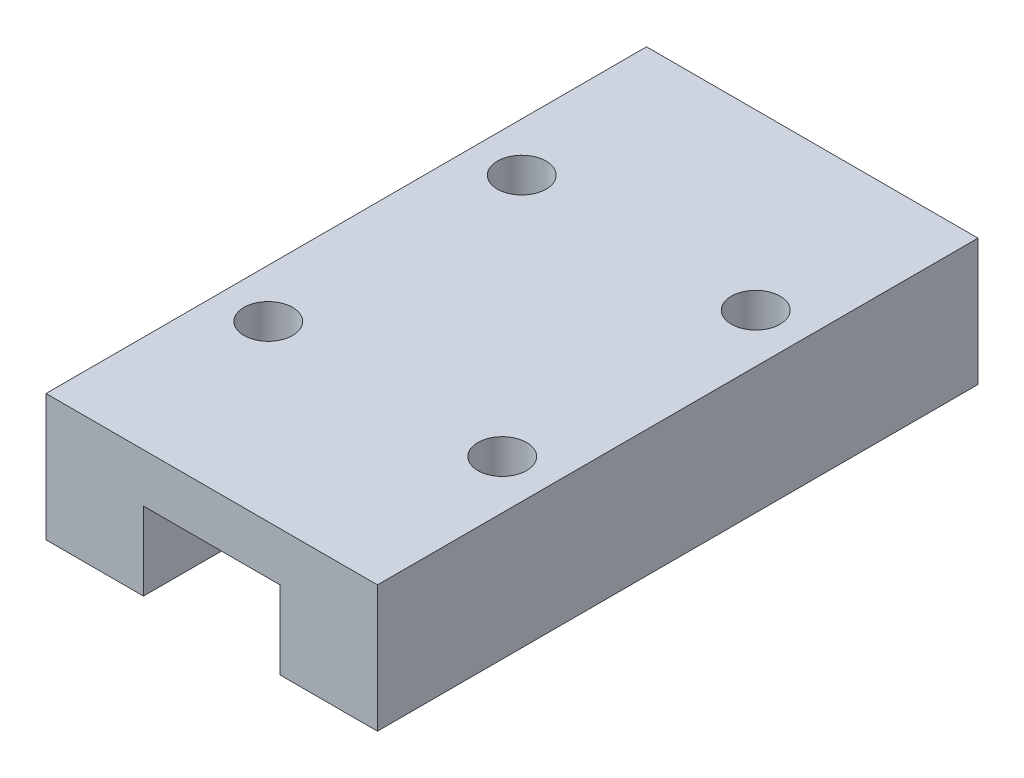
SolidWorks part; units mm, degrees
material "AISI 4340 钢，正火"
ref_plane "前视基准面" through (0, 0, 0) normal (0, 0, 1) x (1, 0, 0)
ref_plane "上视基准面" through (0, 0, 0) normal (0, 1, 0) x (1, 0, 0)
ref_plane "右视基准面" through (0, 0, 0) normal (1, 0, 0) x (0, 0, -1)
sketch "草图1" plane through (0, 0, 0) normal (0, 0, 1) x (1, 0, 0)
  line L0 (0, 0) -> (5, 0)
  line L1 (5, 0) -> (5, 4)
  line L2 (5, 4) -> (12, 4)
  line L3 (12, 4) -> (12, 0)
  line L4 (12, 0) -> (17, 0)
  line L5 (17, 0) -> (17, 6.5)
  line L6 (17, 6.5) -> (0, 6.5)
  line L7 (0, 6.5) -> (0, 0)
  dimension "D1" = 7
  dimension "D2" = 4
  dimension "D3" = 6.5
  dimension "D4" = 17
  dimension "D5" = 5
extrude "凸台-拉伸1" add sketch "草图1" along normal blind 30.8
sketch "草图2" plane through (0, 6.5, 0) normal (0, 1, 0) x (1, 0, 0)
  line L0 (0, -15.4) -> (17, -15.4) construction
  line L1 (0, -30.8) -> (0, 0) construction
  line L2 (17, -30.8) -> (17, 0) construction
  line L3 (8.5, 0) -> (8.5, -30.8) construction
  line L4 (17, 0) -> (0, 0) construction
  line L5 (17, -30.8) -> (0, -30.8) construction
  line L6 (14.5, -15.4) -> (14.5, -10.5187) construction
  line L7 (2.5, -15.4) -> (2.5, -12.8521) construction
  circle A0 centre (14.5, -8.9) radius 1.25
  circle A1 centre (14.5, -21.9) radius 1.25
  circle A2 centre (2.5, -21.9) radius 1.25
  circle A3 centre (2.5, -8.9) radius 1.25
  dimension "D3" = 6.5
  dimension "D4" = 6.5
  dimension "D5" = 2.5
  dimension "D6" = 2.5
  dimension "D1" = 6
  dimension "D2" = 6
extrude "切除-拉伸1" cut sketch "草图2" against normal blind 22.5
